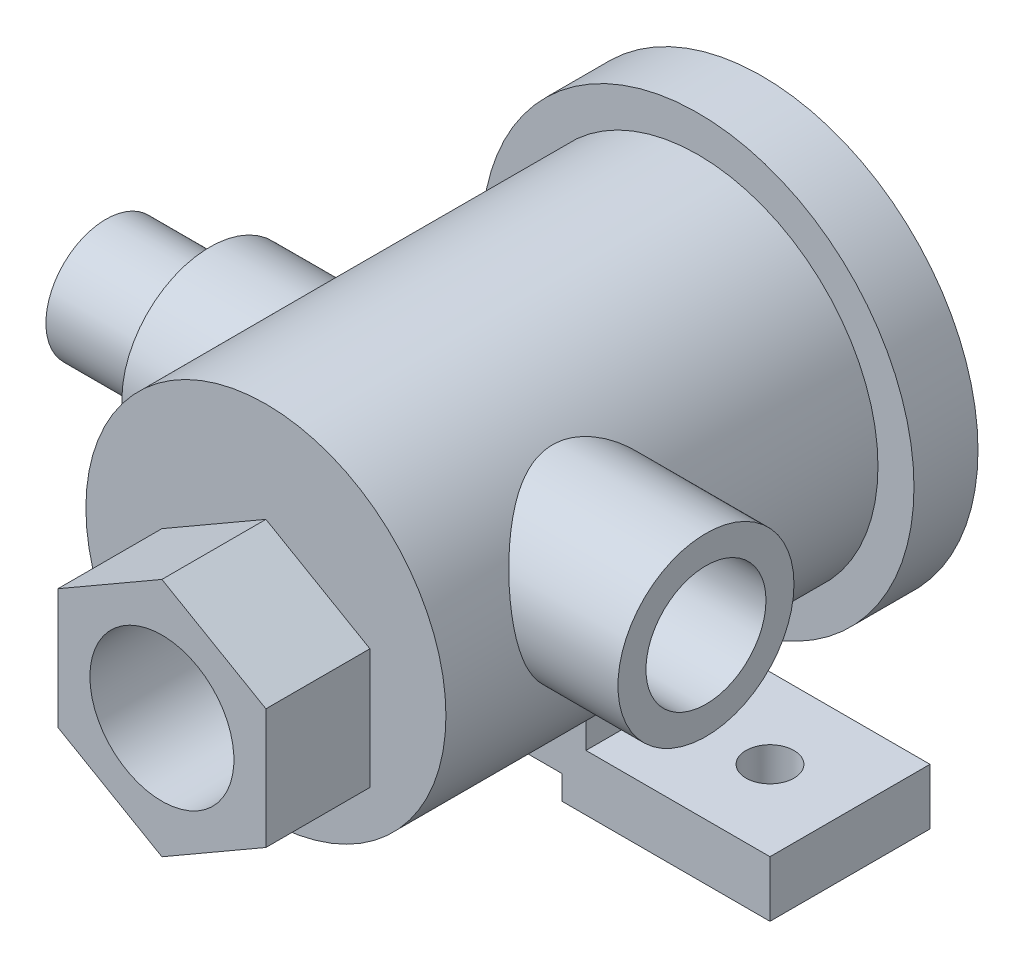
SolidWorks part; units mm, degrees
ref_plane "前视基准面" through (0, 0, 0) normal (0, 0, 1) x (1, 0, 0)
ref_plane "上视基准面" through (0, 0, 0) normal (0, 1, 0) x (1, 0, 0)
ref_plane "右视基准面" through (0, 0, 0) normal (1, 0, 0) x (0, 0, -1)
other "Configuration Table"
sketch "草图1" plane through (0, 0, 0) normal (0, 0, 1) x (1, 0, 0)
  circle A0 centre (0, 0) radius 27
extrude "凸台-拉伸1" add sketch "草图1" against normal blind 8
sketch "草图2" plane through (0, 0, 0) normal (0, 0, 1) x (1, 0, 0)
  circle A0 centre (0, 0) radius 22.5
extrude "凸台-拉伸2" add sketch "草图2" along normal blind 54
sketch "草图3" plane through (0, 0, 54) normal (0, 0, 1) x (1, 0, 0)
  line L0 (0, 0) -> (0, -5) construction
  line L2 (0, 10.0111) -> (-13, 2.5056)
  line L3 (-13, 2.5056) -> (-13, -12.5056)
  line L4 (-13, -12.5056) -> (0, -20.0111)
  line L5 (0, -20.0111) -> (13, -12.5056)
  line L6 (13, -12.5056) -> (13, 2.5056)
  line L7 (13, 2.5056) -> (0, 10.0111)
  circle A0 centre (0, -5) radius 9
  circle A1 centre (0, -5) radius 13 construction
  dimension "D1" = 26
  dimension "D2" = 18
extrude "凸台-拉伸3" add sketch "草图3" along normal blind 13
sketch "草图4" plane through (0, 0, -8) normal (0, 0, -1) x (-1, 0, 0)
  circle A0 centre (0, 0) radius 15
extrude "切除-拉伸1" cut sketch "草图4" against normal blind 56
sketch "草图7" plane through (0, 0, 54) normal (0, 0, 1) x (1, 0, 0)
  circle A1 centre (0, -5) radius 9
  circle A2 centre (0, -5) radius 9
  dimension "D1" = 0
extrude "切除-拉伸2" cut sketch "草图7" against normal up to next
ref_plane "基准面1" through (0, -28, 0) normal (0, 1, 0) x (1, 0, 0)
sketch "草图8" plane through (0, -28, 0) normal (0, 1, 0) x (1, 0, 0)
  line L0 (27, 8) -> (-27, 8) construction
  line L2 (37, -28) -> (-37, -28)
  line L3 (37, -28) -> (37, -8)
  line L4 (37, -8) -> (-37, -8)
  line L5 (-37, -28) -> (-37, -8)
  line L6 (37, -28) -> (-37, -8) construction
  line L7 (37, -8) -> (-37, -28) construction
  point P2 (0, -18)
  dimension "D1" = 74
  dimension "D2" = 20
  dimension "D3" = 26
extrude "凸台-拉伸4" add sketch "草图8" along normal blind 7
sketch "草图9" plane through (0, -28, 0) normal (0, -1, 0) x (1, 0, 0)
  line L0 (-37, 28) -> (37, 28) construction
  line L1 (14, 8) -> (-14, 8)
  line L2 (14, 8) -> (14, 28)
  line L3 (14, 28) -> (-14, 28)
  line L4 (-14, 8) -> (-14, 28)
  line L5 (14, 8) -> (-14, 28) construction
  line L6 (14, 28) -> (-14, 8) construction
  point P0 (0, 18)
  dimension "D1" = 28
extrude "凸台-拉伸5" add sketch "草图9" against normal up to surface (10.3861 mm away)
sketch "草图10" plane through (0, 0, 28) normal (0, 0, 1) x (1, 0, 0)
  line L0 (41.25, -28) -> (-41.25, -28) construction
  line L1 (11, -31) -> (-11, -31)
  line L2 (11, -31) -> (11, -25)
  line L3 (11, -25) -> (-11, -25)
  line L4 (-11, -31) -> (-11, -25)
  line L5 (11, -31) -> (-11, -25) construction
  line L6 (11, -25) -> (-11, -31) construction
  point P0 (0, -28)
  dimension "D1" = 22
  dimension "D2" = 3
extrude "切除-拉伸3" cut sketch "草图10" against normal up to next
ref_plane "基准面2" through (35, 0, 0) normal (1, 0, 0) x (0, 0, -1)
ref_plane "基准面3" through (-27, 0, 0) normal (1, 0, 0) x (0, 0, -1)
sketch "草图12" plane through (35, 0, 0) normal (1, 0, 0) x (0, 0, -1)
  line L0 (-67, -5) -> (-43.8584, -5) construction
  line L1 (-67, -12.5056) -> (-67, 2.5056) construction
  line L2 (8, -27) -> (8, 27) construction
  circle A0 centre (-34, 5) radius 11
  dimension "D1" = 10
  dimension "D3" = 22
  dimension "D2" = 42
extrude "凸台-拉伸7" add sketch "草图12" against normal up to surface (13.0626 mm away)
sketch "草图13" plane through (35, 0, 0) normal (1, 0, 0) x (0, 0, -1)
  circle A0 centre (-34, 5) radius 7.5
  dimension "D1" = 15
sketch "草图15" plane through (-27, 0, 0) normal (1, 0, 0) x (0, 0, -1)
  circle A0 centre (-34, 5) radius 11
  dimension "D1" = 22
extrude "凸台-拉伸8" add sketch "草图15" along normal up to surface (5.0626 mm away)
extrude "切除-拉伸6" cut sketch "草图13" against normal blind 56 contours A0
sketch "草图16" plane through (-27, 0, 0) normal (-1, 0, 0) x (0, 0, 1)
  circle A0 centre (34, 5) radius 7.5
extrude "凸台-拉伸9" add sketch "草图16" along normal blind 13
sketch "草图17" plane through (-40, 0, 0) normal (-1, 0, 0) x (0, 0, 1)
  circle A0 centre (34, 5) radius 4
extrude "切除-拉伸7" cut sketch "草图17" against normal blind 30 contours A0
sketch "草图18" plane through (0, -21, 0) normal (0, 1, 0) x (1, 0, 0)
  line L0 (27, 8) -> (-27, 8) construction
  line L1 (0, -29.7) -> (0, 29.7) construction
  circle A0 centre (-27, -18) radius 3
  circle A1 centre (27, -18) radius 3
  dimension "D1" = 27
  dimension "D3" = 6
  dimension "D2" = 26
extrude "切除-拉伸8" cut sketch "草图18" against normal blind 30
sketch "草图21" plane through (0, 0, 0) normal (1, 0, 0) x (0, 0, -1)
  line L0 (-48, -15) -> (-48, 15) construction
  line L1 (-48, -15) -> (-48, 15)
